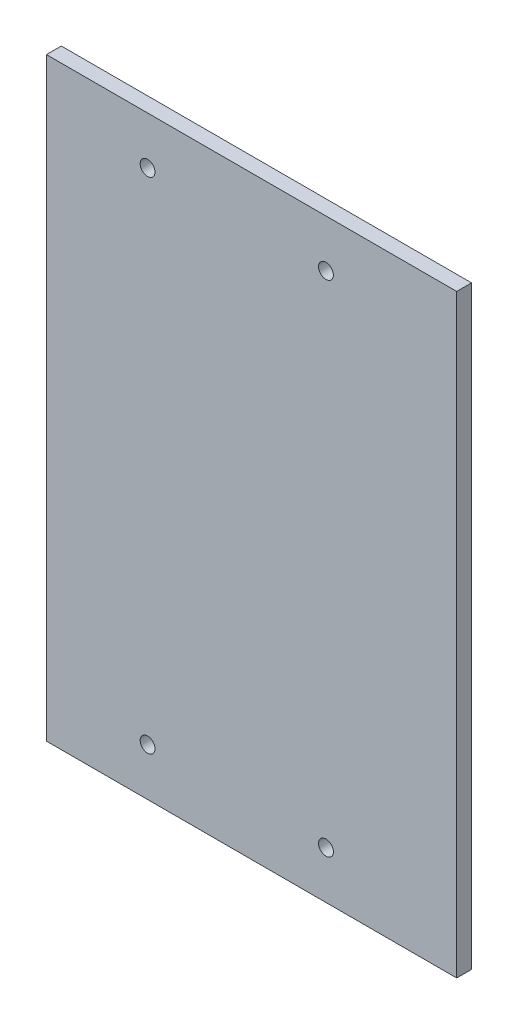
SolidWorks part; units mm, degrees
ref_plane "Plan de face" through (0, 0, 0) normal (0, 0, 1) x (1, 0, 0)
ref_plane "Plan de dessus" through (0, 0, 0) normal (0, 1, 0) x (1, 0, 0)
ref_plane "Plan de droite" through (0, 0, 0) normal (1, 0, 0) x (0, 0, -1)
sketch "Esquisse1" plane through (0, 0, 0) normal (0, 0, 1) x (1, 0, 0)
  line L1 (-55, 100) -> (55, 100)
  line L2 (-55, 100) -> (-55, -100)
  line L3 (-55, -100) -> (55, -100)
  line L4 (55, 100) -> (55, -100)
  line L5 (-55, 100) -> (55, -100) construction
  line L6 (-55, -100) -> (55, 100) construction
  point P0 (0, 0)
  dimension "D1" = 200
  dimension "D2" = 110
extrude "Boss.-Extru.1" add sketch "Esquisse1" along normal blind 5
sketch "Esquisse28" plane through (0, 0, 0) normal (0, 0, -1) x (-1, 0, 0)
  circle A0 centre (20.9808, -84) radius 2.5
  circle A1 centre (-39.0192, -84) radius 2.5
  circle A2 centre (20.9808, 84) radius 2.5
  circle A3 centre (-39.0192, 84) radius 2.5
extrude "Enlèv. mat.-Extru.1" cut sketch "Esquisse28" against normal through all
sketch "Esquisse29" plane through (55, 0, 0) normal (1, 0, 0) x (0, 0, -1)
  line L4 (0, -100) -> (0, 100)
  line L5 (0, 100) -> (-5, 100)
  line L6 (-5, 100) -> (-5, -100)
  line L7 (-5, -100) -> (0, -100)
  line L8 (0, -100) -> (0, 100)
  line L9 (0, 100) -> (-5, 100)
  line L10 (-5, 100) -> (-5, -100)
  line L11 (-5, -100) -> (0, -100)
  dimension "D1" = 0
extrude "Boss.-Extru.2" add sketch "Esquisse29" along normal blind 28
